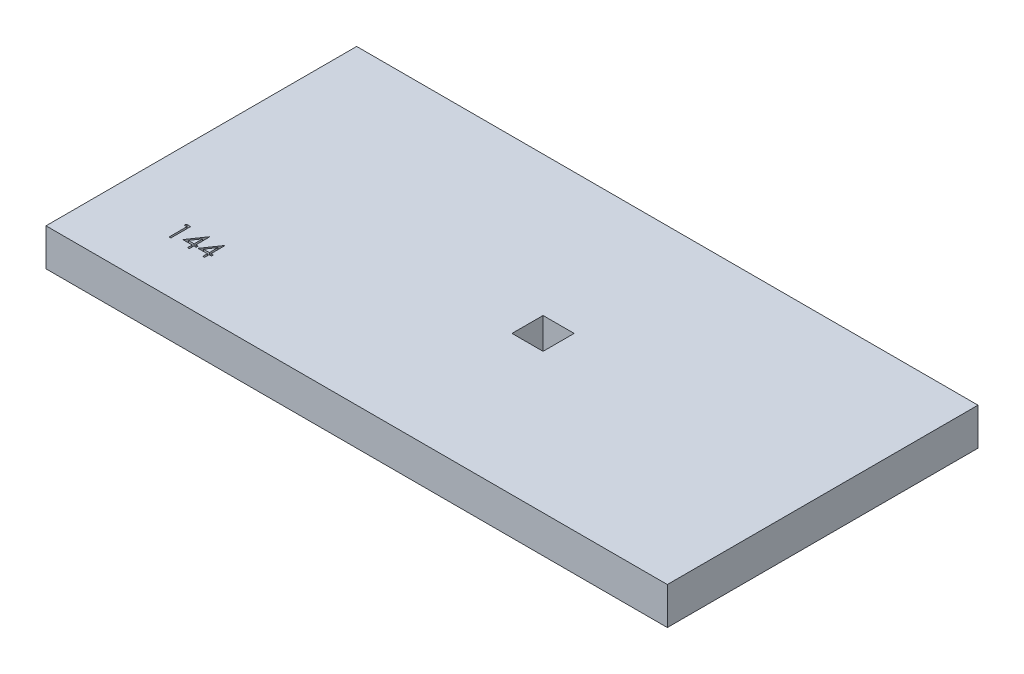
SolidWorks part; units mm, degrees
material "Acrylic (Medium-high impact)"
ref_plane "Front Plane" through (0, 0, 0) normal (0, 0, 1) x (1, 0, 0)
ref_plane "Top Plane" through (0, 0, 0) normal (0, 1, 0) x (1, 0, 0)
ref_plane "Right Plane" through (0, 0, 0) normal (1, 0, 0) x (0, 0, -1)
sketch "Sketch1" plane through (0, 0, 0) normal (0, 1, 0) x (1, 0, 0)
  line L1 (-50, 25) -> (50, 25)
  line L2 (-50, 25) -> (-50, -25)
  line L3 (-50, -25) -> (50, -25)
  line L4 (50, 25) -> (50, -25)
  line L5 (-50, 25) -> (50, -25) construction
  line L6 (-50, -25) -> (50, 25) construction
  dimension "D1" = 100
  dimension "D2" = 50
extrude "Boss-Extrude1" add sketch "Sketch1" along normal blind 6 contours L2 L3 L4 L1
sketch "Sketch2" plane through (0, 6, 0) normal (0, 1, 0) x (1, 0, 0)
  line L1 (2.5, 2.5) -> (7.5, 2.5)
  line L2 (2.5, 2.5) -> (2.5, -2.5)
  line L3 (2.5, -2.5) -> (7.5, -2.5)
  line L4 (7.5, 2.5) -> (7.5, -2.5)
  line L5 (2.5, 2.5) -> (7.5, -2.5) construction
  line L6 (2.5, -2.5) -> (7.5, 2.5) construction
  line L7 (-50, 25) -> (-50, -25) construction
  dimension "D1" = 5
  dimension "D2" = 5
  dimension "D3" = 52.5
extrude "Cut-Extrude1" cut sketch "Sketch2" against normal blind 6
sketch "Sketch3" plane through (0, 6, 0) normal (0, 1, 0) x (1, 0, 0)
  text T0 "144\r\n"
extrude "Cut-Extrude2" cut sketch "Sketch3" against normal blind 1
ref_plane "Plane1" through (-50, 6, -25) normal (1, 0, 0) x (0, 0, -1)
